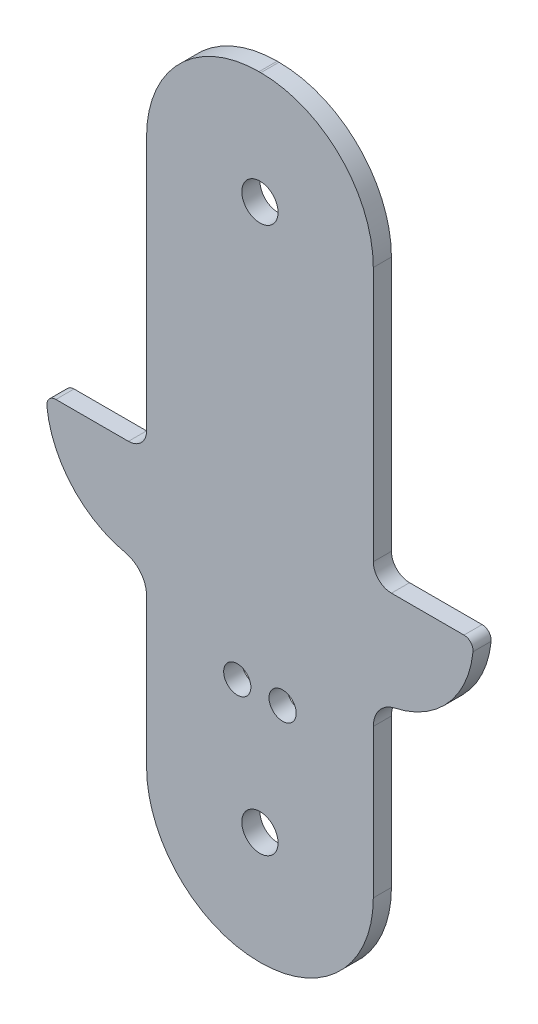
SolidWorks part; units mm, degrees
ref_plane "Front Plane" through (0, 0, 0) normal (0, 0, 1) x (1, 0, 0)
ref_plane "Top Plane" through (0, 0, 0) normal (0, 1, 0) x (1, 0, 0)
ref_plane "Right Plane" through (0, 0, 0) normal (1, 0, 0) x (0, 0, -1)
sketch "Sketch1" plane through (0, 0, 0) normal (0, 0, 1) x (1, 0, 0)
  line L0 (0, 42.5) -> (70.2451, 42.5) construction
  line L1 (12.4, 0) -> (12.6, 0)
  line L2 (0, 12.4) -> (0, 28.7741)
  line L3 (12.4, 85) -> (12.6, 85)
  line L4 (25, 12.4) -> (25, 28.7741)
  line L5 (-2, 42.5) -> (-10, 42.5)
  line L6 (12.5, 0) -> (12.5, 34.9925) construction
  line L7 (27, 42.5) -> (35, 42.5)
  line L8 (0, 44.5) -> (0, 72.6)
  line L9 (25, 44.5) -> (25, 72.6)
  arc A0 (-10.995, 41.4005) -> (-2.3594, 31.705) centre (0, 42.5) ccw
  arc A1 (-10, 42.5) -> (-10.995, 41.4005) centre (-10, 41.5) ccw
  arc A2 (35, 42.5) -> (35.995, 41.4005) centre (35, 41.5) cw
  arc A3 (35.995, 41.4005) -> (27.3594, 31.705) centre (25, 42.5) cw
  circle A4 centre (12.5, 12.4) radius 7.5 construction
  arc A5 (27.3594, 31.705) -> (25, 28.7741) centre (28, 28.7741) ccw
  arc A6 (-2.3594, 31.705) -> (0, 28.7741) centre (-3, 28.7741) cw
  arc A7 (27, 42.5) -> (25, 44.5) centre (27, 44.5) cw
  arc A8 (-2, 42.5) -> (0, 44.5) centre (-2, 44.5) ccw
  arc A9 (12.6, 0) -> (25, 12.4) centre (12.6, 12.4) ccw
  arc A10 (12.4, 0) -> (0, 12.4) centre (12.4, 12.4) cw
  arc A11 (12.6, 85) -> (25, 72.6) centre (12.6, 72.6) cw
  arc A12 (0, 72.6) -> (12.4, 85) centre (12.4, 72.6) cw
  circle A13 centre (12.5, 72.6) radius 2
  circle A14 centre (12.5, 12.4) radius 2
  circle A15 centre (10, 25.7672) radius 1.5
  circle A16 centre (15, 25.7672) radius 1.5
  point P23 (25, 31.4501)
  point P26 (0, 31.4501)
  point P37 (0, 0)
  point P40 (25, 85)
  point P43 (0, 85)
  dimension "D3" = 1
  dimension "D4" = 15
  dimension "D5" = 3
  dimension "D6" = 2
  dimension "D7" = 12.4
  dimension "D8" = 12.4
  dimension "D9" = 4
  dimension "D10" = 4
  dimension "D11" = 3
  dimension "D12" = 3
  dimension "D1" = 85
  dimension "D2" = 25
  dimension "D13" = 2.5
  dimension "D14" = 2.5
  dimension "D15" = 8
  dimension "D16" = 42.5
extrude "Boss-Extrude1" add sketch "Sketch1" along normal blind 2
